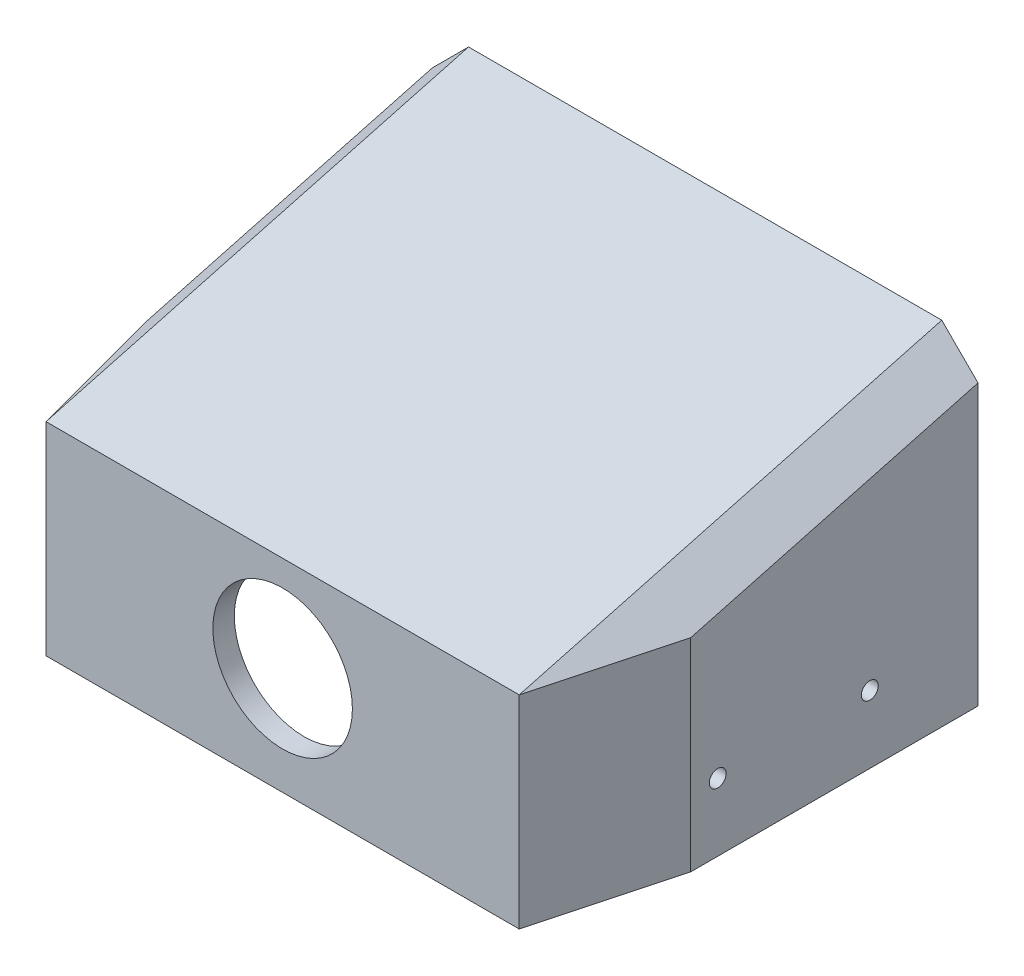
SolidWorks part; units mm, degrees
ref_plane "Front Plane" through (0, 0, 0) normal (0, 0, 1) x (1, 0, 0)
ref_plane "Top Plane" through (0, 0, 0) normal (0, 1, 0) x (1, 0, 0)
ref_plane "Right Plane" through (0, 0, 0) normal (1, 0, 0) x (0, 0, -1)
sketch "Sketch1" plane through (0, 0, 0) normal (0, 1, 0) x (1, 0, 0)
  line L0 (-103.4936, 62.5) -> (103.4936, 62.5)
  line L1 (103.4936, 62.5) -> (70, -62.5)
  line L2 (70, -62.5) -> (-70, -62.5)
  line L3 (0, -62.5) -> (0, 62.5) construction
  line L4 (-103.4936, 62.5) -> (-70, -62.5)
  point P2 (0, 0)
  dimension "D1" = 75
  dimension "D2" = 70
  dimension "D3" = 125
extrude "Boss-Extrude1" add sketch "Sketch1" along normal blind 60
sketch "Sketch2" plane through (0, 0, 0) normal (1, 0, 0) x (0, 0, -1)
  line L0 (-62.5, 60) -> (62.5, 93.4936)
  line L1 (62.5, 93.4936) -> (62.5, 60)
  line L2 (62.5, 60) -> (-62.5, 60)
  dimension "D1" = 15
extrude "Boss-Extrude2" add sketch "Sketch2" along normal up to vertex (70 mm away) and the other way up to vertex (70 mm away)
sketch "Sketch4" plane through (0, 0, -62.5) normal (0, 0, -1) x (-1, 0, 0)
  line L0 (-70, 93.4936) -> (-70, 60)
  line L1 (-70, 60) -> (-103.4936, 60)
  line L2 (-103.4936, 60) -> (-70, 93.4936)
  line L3 (0, 0) -> (0, 93.4936) construction
  line L4 (-70, 93.4936) -> (70, 93.4936) construction
  line L5 (70, 60) -> (103.4936, 60)
  line L6 (70, 93.4936) -> (70, 60)
  line L7 (103.4936, 60) -> (70, 93.4936)
ref_plane "Plane1" through (70.8307, 70.8307, 18.979) normal (0.6947, 0.6947, 0.1862) x (0.7187, -0.6601, -0.2185)
ref_plane "Plane2" through (-70.8307, 70.8307, 18.979) normal (-0.6947, 0.6947, 0.1862) x (0.7187, 0.6601, 0.2185)
extrude "Boss-Extrude3" add sketch "Sketch4" against normal up to vertex (125 mm away)
sketch "Sketch5" plane through (70.8307, 70.8307, 18.979) normal (0.6947, 0.6947, 0.1862) x (0.7187, -0.6601, -0.2185)
  line L1 (-88.9, 88.9) -> (88.9, 88.9)
  line L2 (-88.9, 88.9) -> (-88.9, -88.9)
  line L3 (-88.9, -88.9) -> (88.9, -88.9)
  line L4 (88.9, 88.9) -> (88.9, -88.9)
  line L5 (-88.9, 88.9) -> (88.9, -88.9) construction
  line L6 (-88.9, -88.9) -> (88.9, 88.9) construction
  point P0 (0, 0)
  dimension "D1" = 177.8
  dimension "D2" = 177.8
extrude "Cut-Extrude1" cut sketch "Sketch5" along normal through all
sketch "Sketch6" plane through (-70.8307, 70.8307, 18.979) normal (-0.6947, 0.6947, 0.1862) x (0.7187, 0.6601, 0.2185)
  line L1 (-88.9, 88.9) -> (88.9, 88.9)
  line L2 (-88.9, 88.9) -> (-88.9, -88.9)
  line L3 (-88.9, -88.9) -> (88.9, -88.9)
  line L4 (88.9, 88.9) -> (88.9, -88.9)
  line L5 (-88.9, 88.9) -> (88.9, -88.9) construction
  line L6 (-88.9, -88.9) -> (88.9, 88.9) construction
  point P0 (0, 0)
  dimension "D1" = 177.8
  dimension "D2" = 177.8
extrude "Cut-Extrude2" cut sketch "Sketch6" along normal through all
sketch "Sketch10" plane through (0, 0, 0) normal (0, 1, 0) x (1, 0, 0)
  line L0 (0, 0) -> (0, -62.5) construction
  line L1 (-70, -62.5) -> (70, -62.5) construction
  line L2 (-103.4936, 62.5) -> (-70, -62.5) construction
  line L3 (-80.718, -22.5) -> (-120, -22.5)
  line L4 (-80.718, -22.5) -> (-80.718, 67.5)
  line L5 (-80.718, 67.5) -> (-120, 67.5)
  line L6 (-120, -22.5) -> (-120, 67.5)
  line L7 (80.718, 67.5) -> (120, 67.5)
  line L8 (120, -22.5) -> (120, 67.5)
  line L9 (80.718, -22.5) -> (120, -22.5)
  line L10 (80.718, -22.5) -> (80.718, 67.5)
  dimension "D1" = 40
  dimension "D2" = 90
  dimension "D3" = 120
extrude "Cut-Extrude5" cut sketch "Sketch10" against normal through all from vertex at 93.4937 starting at point (70, 93.4937, -62.5)
shell "Shell1" thickness 6.35
sketch "Sketch7" plane through (0, 0, -62.5) normal (0, 0, -1) x (-1, 0, 0)
  circle A0 centre (0, 31.75) radius 20.64
  dimension "D1" = 41.28
  dimension "D2" = 31.75
extrude "Cut-Extrude3" cut sketch "Sketch7" against normal blind 25.4
sketch "Sketch8" plane through (0, 0, 62.5) normal (0, 0, 1) x (1, 0, 0)
  circle A0 centre (0, 31.75) radius 20.64
  circle A1 centre (0, 31.75) radius 20.64 construction
extrude "Cut-Extrude4" cut sketch "Sketch8" against normal blind 25.4
sketch "Sketch11" plane through (0, 0, 0) normal (1, 0, 0) x (0, 0, -1)
  line L0 (-22.5, 0) -> (-22.5, 60) construction
  line L1 (62.5, 0) -> (-22.5, 0) construction
  line L2 (-14.5, 20) -> (30.5, 20) construction
  circle A0 centre (-14.5, 20) radius 2.5
  circle A1 centre (30.5, 20) radius 2.5
  dimension "D1" = 5
  dimension "D2" = 8
  dimension "D3" = 20
  dimension "D4" = 45
extrude "Cut-Extrude6" cut sketch "Sketch11" against normal through all both and the other way through all
sketch "Sketch9" plane through (0, 0, 0) normal (0, 1, 0) x (1, 0, 0)
  line L3 (-103.4936, 62.5) -> (-97.1436, 62.5)
  line L4 (-103.4936, 62.5) -> (-70, 62.5) construction
  line L5 (-97.1436, 62.5) -> (-70, -62.5)
  line L6 (-70, -62.5) -> (-103.4936, -62.5)
  line L7 (-103.4936, -62.5) -> (-103.4936, 62.5)
  line L8 (0, 0) -> (0, -62.5) construction
  line L9 (-70, -62.5) -> (70, -62.5) construction
  line L10 (70, -62.5) -> (103.4936, -62.5)
  line L11 (97.1436, 62.5) -> (70, -62.5)
  line L12 (103.4936, 62.5) -> (97.1436, 62.5)
  line L13 (103.4936, -62.5) -> (103.4936, 62.5)
  dimension "D1" = 6.35
